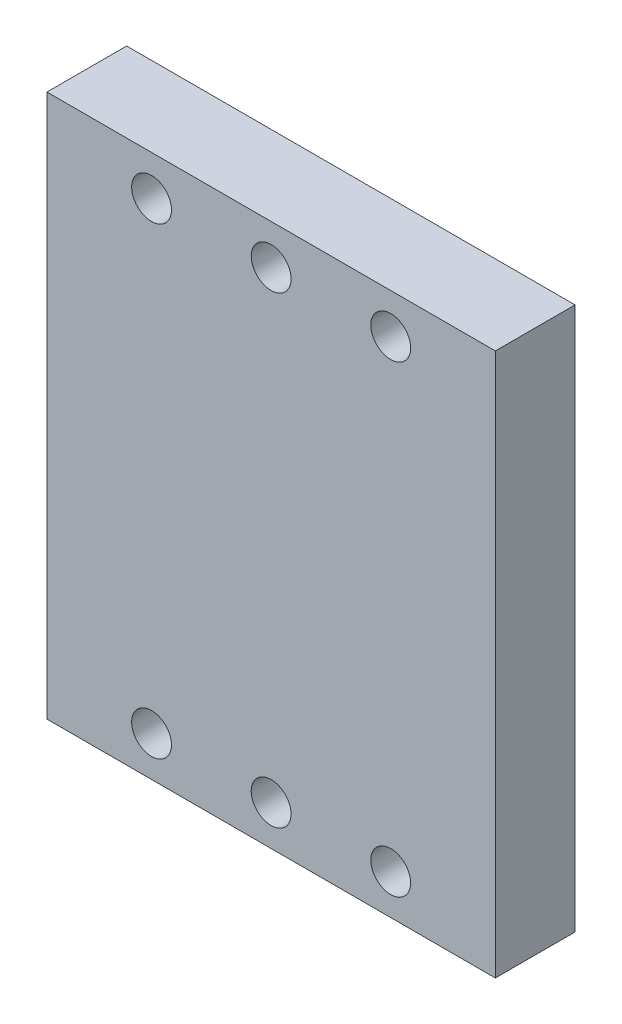
SolidWorks part; units mm, degrees
ref_plane "Front" through (0, 0, 0) normal (0, 0, 1) x (1, 0, 0)
ref_plane "Top" through (0, 0, 0) normal (0, 1, 0) x (1, 0, 0)
ref_plane "Right" through (0, 0, 0) normal (1, 0, 0) x (0, 0, -1)
sketch "Esquisse1" plane through (0, 0, 0) normal (0, 0, 1) x (1, 0, 0)
  line L1 (0, 0) -> (45, 0)
  line L2 (0, 0) -> (0, 54.5)
  line L3 (0, 54.5) -> (45, 54.5)
  line L4 (45, 0) -> (45, 54.5)
  dimension "D1" = 45
  dimension "D2" = 54.5
extrude "Boss.-Extru.1" add sketch "Esquisse1" along normal blind 8
sketch "Esquisse2" plane through (0, 0, 8) normal (0, 0, 1) x (1, 0, 0)
  line L0 (0, 4) -> (45, 4) construction
  line L1 (0, 54.5) -> (0, 0) construction
  line L2 (45, 0) -> (45, 54.5) construction
  line L3 (0, 0) -> (45, 0) construction
  line L4 (22.5, 0) -> (22.5, 4) construction
  line L5 (0, 27.25) -> (45, 27.25) construction
  line L6 (22.5, 54.5) -> (22.5, 50.5) construction
  line L7 (0, 50.5) -> (45, 50.5) construction
  circle A0 centre (10.5, 4) radius 2
  circle A1 centre (34.5, 4) radius 2
  circle A2 centre (22.5, 4) radius 2
  circle A3 centre (22.5, 50.5) radius 2
  circle A4 centre (34.5, 50.5) radius 2
  circle A5 centre (10.5, 50.5) radius 2
  dimension "D1" = 4
  dimension "D3" = 12
  dimension "D4" = 46.5
  dimension "D2" = 4
extrude "Enlèv. mat.-Extru.1" cut sketch "Esquisse2" against normal up to vertex (8 mm away)
